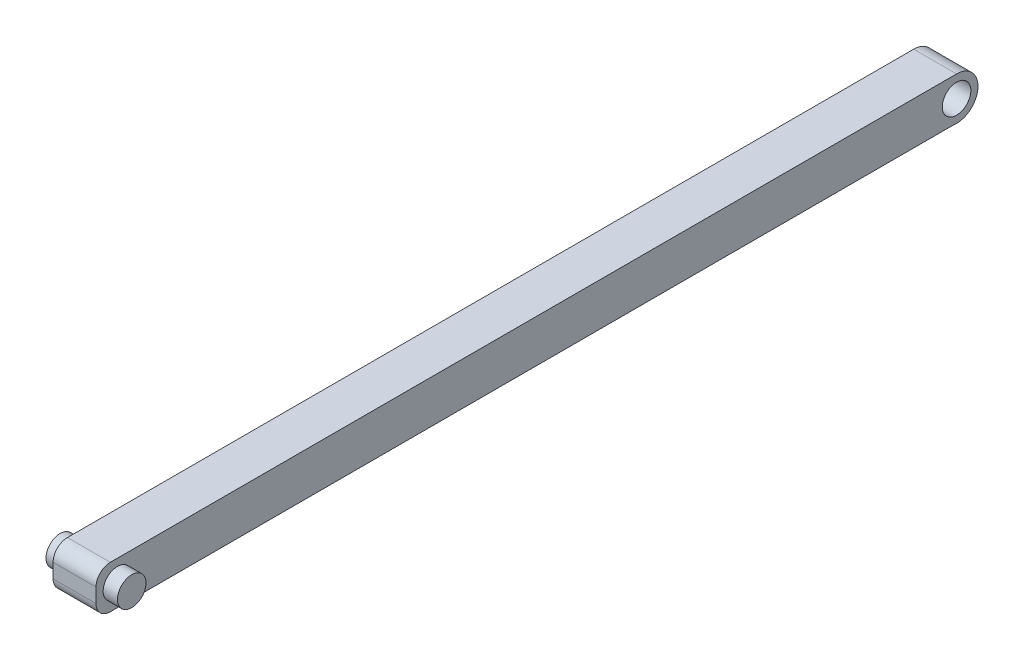
SolidWorks part; units mm, degrees
ref_plane "Front Plane" through (0, 0, 0) normal (0, 0, 1) x (1, 0, 0)
ref_plane "Top Plane" through (0, 0, 0) normal (0, 1, 0) x (1, 0, 0)
ref_plane "Right Plane" through (0, 0, 0) normal (1, 0, 0) x (0, 0, -1)
sketch "Sketch1" plane through (0, 0, 0) normal (1, 0, 0) x (0, 0, -1)
  line L0 (95, 0) -> (100, 0) construction
  line L1 (-201.0091, 7.5687) -> (100, 7.5)
  line L2 (-201.0091, -7.4313) -> (98.9909, -7.4318)
  line L3 (-201.0091, 7.5687) -> (-201.0091, -7.4313)
  arc A1 (98.9909, -7.4318) -> (100, 7.5) centre (100, 0) ccw
  circle A2 centre (100, 0) radius 5
  point P0 (-202.0181, -14.8636)
  point P3 (-16.88, 0)
  dimension "D1" = 10
  dimension "25" = 7.5
  dimension "D2" = 300
  dimension "D3" = 100
  dimension "D4" = 15
extrude "Boss-Extrude1" add sketch "Sketch1" along normal blind 15
sketch "Sketch4" plane through (15, 0, 0) normal (1, 0, 0) x (0, 0, -1)
  line L0 (100, 7.5) -> (-201.0091, 7.5687) construction
  line L1 (-201.0091, 7.5687) -> (-201.0091, -7.4313) construction
  circle A0 centre (-193.5091, 0.067) radius 5
  dimension "D1" = 10
  dimension "D2" = 7.5
  dimension "D3" = 7.5
extrude "Boss-Extrude3" add sketch "Sketch4" along normal blind 5 and the other way blind 20
fillet "Fillet1" radius 5 2 edges at (7.5, -7.4313, 201.0091) (7.5, 7.5687, 201.0091)
